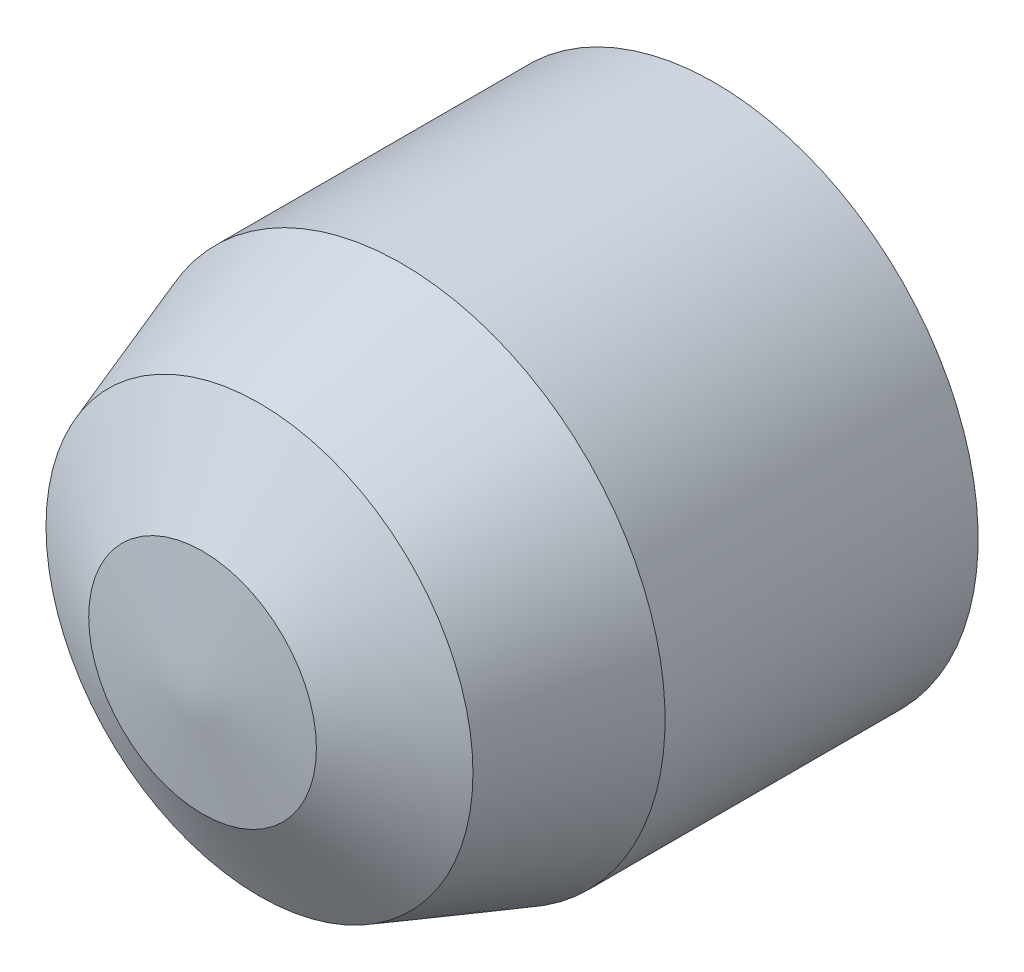
SolidWorks part; units mm, degrees
material "ABS PC"
ref_plane "Front Plane" through (0, 0, 0) normal (0, 0, 1) x (1, 0, 0)
ref_plane "Top Plane" through (0, 0, 0) normal (0, 1, 0) x (1, 0, 0)
ref_plane "Right Plane" through (0, 0, 0) normal (1, 0, 0) x (0, 0, -1)
ref_plane "Plane Y=225" through (0, 225, 0) normal (0, 1, 0) x (1, 0, 0)
sketch "Revolve profile 1" plane through (0, 225, 0) normal (0, 1, 0) x (1, 0, 0)
  line L0 (860, -896) -> (860, -822)
  line L1 (860, -822) -> (897, -822)
  line L2 (897, -822) -> (897, -866)
  line L3 (897, -866) -> (890, -886)
  line L4 (890, -886) -> (876, -894)
  line L5 (876, -894) -> (860, -896)
  line L6 (860, -817) -> (860, -901) construction
  dimension "D1" = 7
  dimension "D2" = 21
  dimension "D3" = 37
  dimension "D4" = 44
  dimension "D5" = 64
  dimension "D6" = 72
revolve "Revolve 1" add sketch "Revolve profile 1" angle 360 about L6
